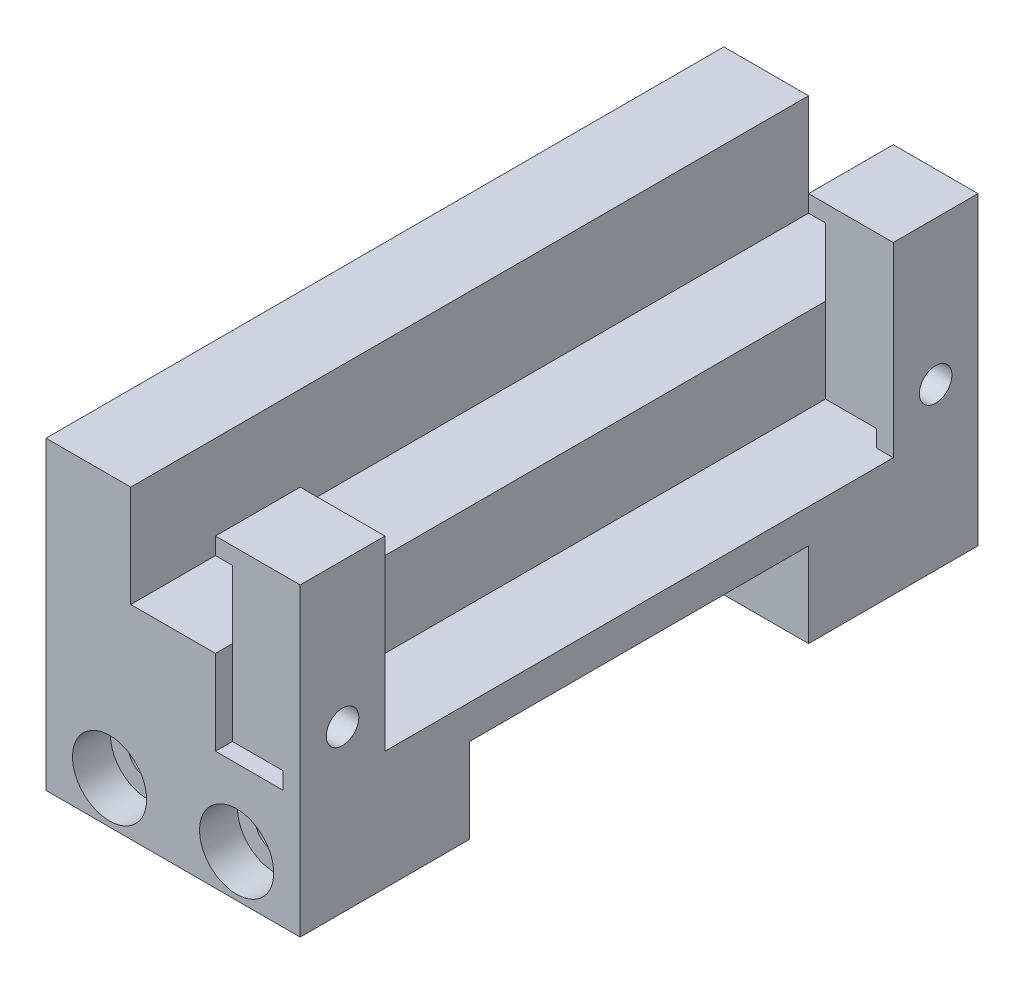
SolidWorks part; units mm, degrees
material "6061 Alloy"
ref_plane "Front Plane" through (0, 0, 0) normal (0, 0, 1) x (1, 0, 0)
ref_plane "Top Plane" through (0, 0, 0) normal (0, 1, 0) x (1, 0, 0)
ref_plane "Right Plane" through (0, 0, 0) normal (1, 0, 0) x (0, 0, -1)
sketch "Sketch2" plane through (0, 0, 0) normal (0, 0, 1) x (1, 0, 0)
  line L1 (-9.525, -9.525) -> (9.525, -9.525)
  line L2 (-9.525, -9.525) -> (-9.525, 9.525)
  line L3 (-9.525, 9.525) -> (9.525, 9.525)
  line L4 (9.525, -9.525) -> (9.525, 9.525)
  line L5 (-9.525, -9.525) -> (9.525, 9.525) construction
  line L6 (-9.525, 9.525) -> (9.525, -9.525) construction
  point P0 (0, 0)
  dimension "D1" = 19.05
  dimension "D2" = 19.05
extrude "Boss-Extrude1" add sketch "Sketch2" along normal mid plane 50.8
sketch "Sketch4" plane through (-1.5069, 3.1105, 25.4) normal (0, 0, 1) x (1, 0, 0)
  line L1 (-1.6681, 6.4145) -> (4.6819, 6.4145)
  line L2 (-1.6681, 6.4145) -> (-1.6681, -3.7455)
  line L3 (-1.6681, -3.7455) -> (4.6819, -3.7455)
  line L4 (4.6819, 6.4145) -> (4.6819, -3.7455)
  line L7 (-8.0181, 6.4145) -> (11.0319, 6.4145)
  line L8 (-8.0181, 6.4145) -> (-8.0181, 3.8745)
  line L9 (-8.0181, 3.8745) -> (11.0319, 3.8745)
  line L10 (11.0319, 6.4145) -> (11.0319, 3.8745)
  line L11 (11.0319, 6.4145) -> (-8.0181, 6.4145) construction
  line L12 (11.0319, -12.6355) -> (11.0319, 6.4145) construction
  line L13 (-8.0181, 6.4145) -> (-8.0181, -12.6355) construction
  dimension "D1" = 6.35
  dimension "D2" = 0
  dimension "D3" = 10.16
  dimension "D4" = 2.54
  dimension "D5" = 0
  dimension "D6" = 0
  dimension "D7" = 0
  dimension "D8" = 6.35
extrude "Cut-Extrude1" cut sketch "Sketch4" against normal through all
sketch "Sketch6" plane through (-1.5069, 3.1105, 25.4) normal (0, 0, 1) x (1, 0, 0)
  line L0 (4.6819, 3.8745) -> (4.6819, -3.7455) construction
  line L5 (4.6819, 2.6045) -> (5.9519, 2.6045)
  line L6 (4.6819, 2.6045) -> (4.6819, -10.0955)
  line L7 (4.6819, -10.0955) -> (5.9519, -10.0955)
  line L8 (5.9519, 2.6045) -> (5.9519, -10.0955)
  line L12 (4.6819, -10.0955) -> (9.7619, -10.0955)
  line L13 (4.6819, -10.0955) -> (4.6819, -8.8255)
  line L14 (4.6819, -8.8255) -> (9.7619, -8.8255)
  line L15 (9.7619, -10.0955) -> (9.7619, -8.8255)
  line L16 (4.6819, 3.8745) -> (11.0319, 3.8745) construction
  line L17 (-8.0181, -12.6355) -> (11.0319, -12.6355) construction
  line L18 (11.0319, -12.6355) -> (11.0319, 3.8745) construction
  point P7 (5.3169, -10.0955)
  dimension "D1" = 1.27
  dimension "D2" = 1.27
  dimension "D3" = 2.54
  dimension "D4" = 1.27
  dimension "D5" = 1.27
extrude "Cut-Extrude2" cut sketch "Sketch6" against normal through all
sketch "Sketch7" plane through (9.525, 0, 0) normal (1, 0, 0) x (0, 0, -1)
  line L0 (25.4, 6.985) -> (-25.4, 6.985) construction
  line L1 (-19.05, 6.985) -> (19.05, 6.985)
  line L2 (-19.05, 6.985) -> (-19.05, -6.985)
  line L3 (-19.05, -6.985) -> (19.05, -6.985)
  line L4 (19.05, 6.985) -> (19.05, -6.985)
  line L5 (-25.4, -9.525) -> (-25.4, 6.985) construction
  line L6 (25.4, -9.525) -> (25.4, 6.985) construction
  line L7 (-25.4, -9.525) -> (25.4, -9.525) construction
  dimension "D1" = 6.35
  dimension "D2" = 6.35
  dimension "D3" = 2.54
extrude "Cut-Extrude3" cut sketch "Sketch7" against normal up to surface (6.35 mm away) up to face at (3.175, 6.35, 0)
sketch "Sketch8" plane through (0, 0, 25.4) normal (0, 0, 1) x (1, 0, 0)
  line L0 (-9.525, -9.525) -> (9.525, -9.525)
  line L1 (-9.525, -9.525) -> (-9.525, -15.875)
  line L2 (9.525, -9.525) -> (9.525, -15.875)
  line L3 (-9.525, -15.875) -> (9.525, -15.875)
  dimension "D1" = 6.35
extrude "Boss-Extrude2" add sketch "Sketch8" against normal blind 12.7
mirror "Mirror1" about plane through (0, 0, 0) normal (0, 0, 1) of "Boss-Extrude2"
hole_wizard "CBORE for #4 Socket Head Cap Screw1" positions "Sketch9" profile "Sketch10" counterbore size "#4" standard "ANSI Inch"
sketch "Sketch9" plane through (0, 0, 25.4) normal (0, 0, 1) x (1, 0, 0)
  line L0 (-9.525, -15.875) -> (9.525, -15.875) construction
  line L1 (-9.525, 6.985) -> (-9.525, -15.875) construction
  line L2 (9.525, -15.875) -> (9.525, 6.985) construction
  point P0 (-4.7625, -12.7)
  point P2 (4.7625, -12.7)
  dimension "D1" = 3.175
  dimension "D2" = 4.7625
  dimension "D3" = 4.7625
  dimension "D4" = 3.175
sketch "Sketch10" plane through (-4.7625, -12.7, 25.4) normal (1, 0, 0) x (0, -1, 0)
  line L0 (0, 0) -> (0, 12.7)
  line L1 (0, 12.7) -> (1.4732, 12.7)
  line L3 (1.4732, 12.7) -> (1.4732, 2.8448)
  line L4 (1.4732, 2.8448) -> (2.7788, 2.8448)
  line L5 (2.7788, 2.8448) -> (2.7788, 0)
  line L7 (2.7788, 0) -> (0, 0)
  line L11 (0, -6.35) -> (0, 107.95) construction
  dimension "Thru Hole Dia." = 2.9464
  dimension "Thru Hole Depth" = 12.7
  dimension "C'Bore Dia." = 5.5575
  dimension "C'Bore Depth" = 2.8448
hole_wizard "#2 Clearance Hole1" positions "Sketch13" profile "Sketch14" hole size "#2" standard "ANSI Inch"
sketch "Sketch13" plane through (9.525, 0, 0) normal (1, 0, 0) x (0, 0, -1)
  line L0 (-25.4, -15.875) -> (-25.4, 6.985) construction
  line L1 (25.4, -15.875) -> (25.4, 6.985) construction
  point P0 (-22.225, -3.81)
  point P2 (22.225, -3.81)
  dimension "D1" = 3.175
  dimension "D2" = 3.175
  dimension "D3" = 3.175
  dimension "D4" = 3.175
sketch "Sketch14" plane through (9.525, -3.81, 22.225) normal (0, 1, 0) x (0, 0, -1)
  line L0 (0, 0) -> (0, 5.08)
  line L1 (0, 5.08) -> (1.2192, 5.08)
  line L2 (1.2192, 5.08) -> (1.2192, 0)
  line L5 (1.2192, 0) -> (0, 0)
  line L11 (0, -6.35) -> (0, 107.95) construction
  dimension "Thru Hole Dia." = 2.4384
  dimension "Thru Hole Depth" = 5.08
hole_wizard "#2-56 Tapped Hole1" positions "Sketch15" profile "Sketch16" tap size "#2-56" standard "ANSI Inch" end condition through all
sketch "Sketch15" plane through (3.175, 0, 0) normal (1, 0, 0) x (0, 0, -1)
  line L0 (25.4, -0.635) -> (-25.4, -0.635) construction
  line L1 (-25.4, -0.635) -> (-25.4, -6.985) construction
  line L2 (25.4, -0.635) -> (25.4, -6.985) construction
  line L3 (25.4, -0.635) -> (-25.4, -0.635) construction
  point P0 (-22.225, -3.81)
  point P2 (22.225, -3.81)
  dimension "D1" = 3.175
  dimension "D2" = 3.175
  dimension "D3" = 3.175
  dimension "D4" = 3.175
sketch "Sketch16" plane through (3.175, -3.81, 22.225) normal (0, 1, 0) x (0, 0, -1)
  line L0 (0, 0) -> (0, 12.7)
  line L1 (0, 12.7) -> (0.889, 12.7)
  line L2 (0.889, 12.7) -> (0.889, 0)
  line L5 (0.889, 0) -> (0, 0)
  line L11 (0, -6.35) -> (0, 107.95) construction
  dimension "Thru Tap Drill Dia." = 1.778
  dimension "Thru Tap Drill Depth" = 12.7
cosmetic thread "Hole Thread1" parameters "D2"=2.1844
cosmetic thread "Hole Thread2" parameters "D2"=2.1844
